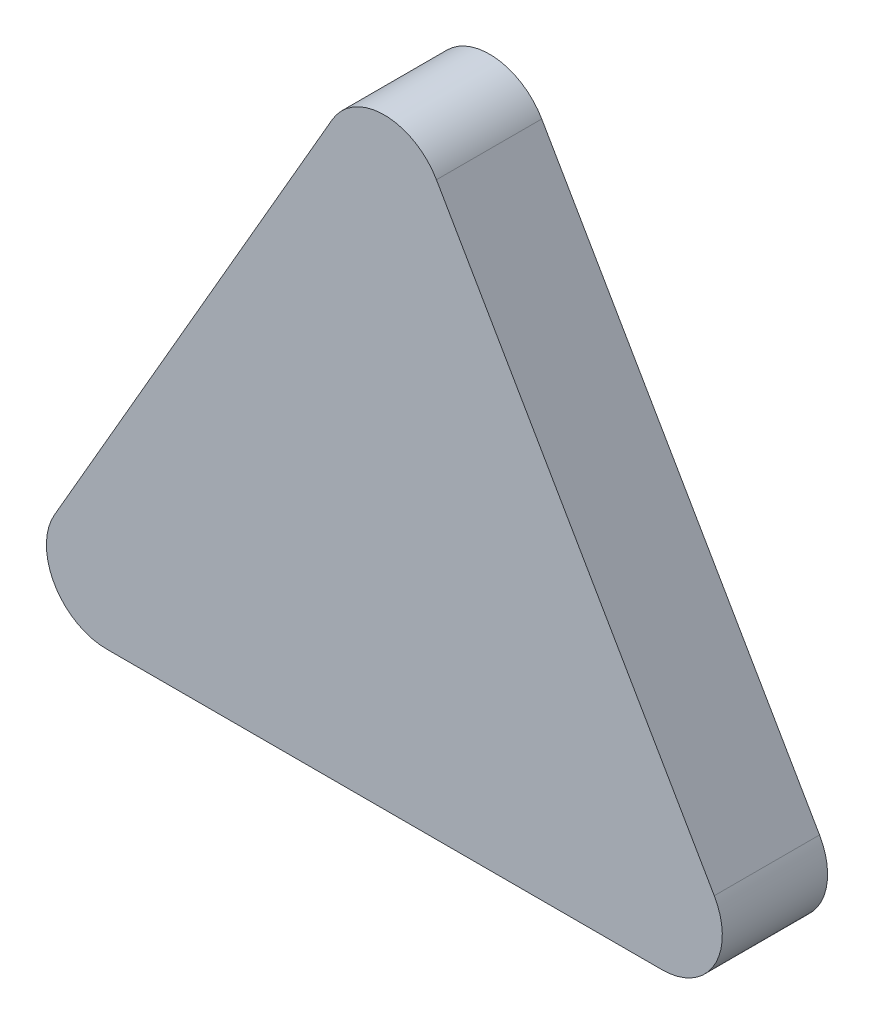
SolidWorks part; units mm, degrees
ref_plane "Plan de face" through (0, 0, 0) normal (0, 0, 1) x (1, 0, 0)
ref_plane "Plan de dessus" through (0, 0, 0) normal (0, 1, 0) x (1, 0, 0)
ref_plane "Plan de droite" through (0, 0, 0) normal (1, 0, 0) x (0, 0, -1)
sketch "Esquisse1" plane through (0, 0, 0) normal (0, 0, 1) x (1, 0, 0)
  line L0 (-12.7, 0) -> (12.7, 0)
  line L1 (12.7, 0) -> (0, 21.997)
  line L2 (0, 21.997) -> (-12.7, 0)
  dimension "D1" = 25.4
extrude "Boss.-Extru.1" add sketch "Esquisse1" along normal blind 3.5
fillet "Congé1" radius 2 3 edges at (12.7, 0, 1.75) (-12.7, 0, 1.75) (0, 21.997, 1.75)
